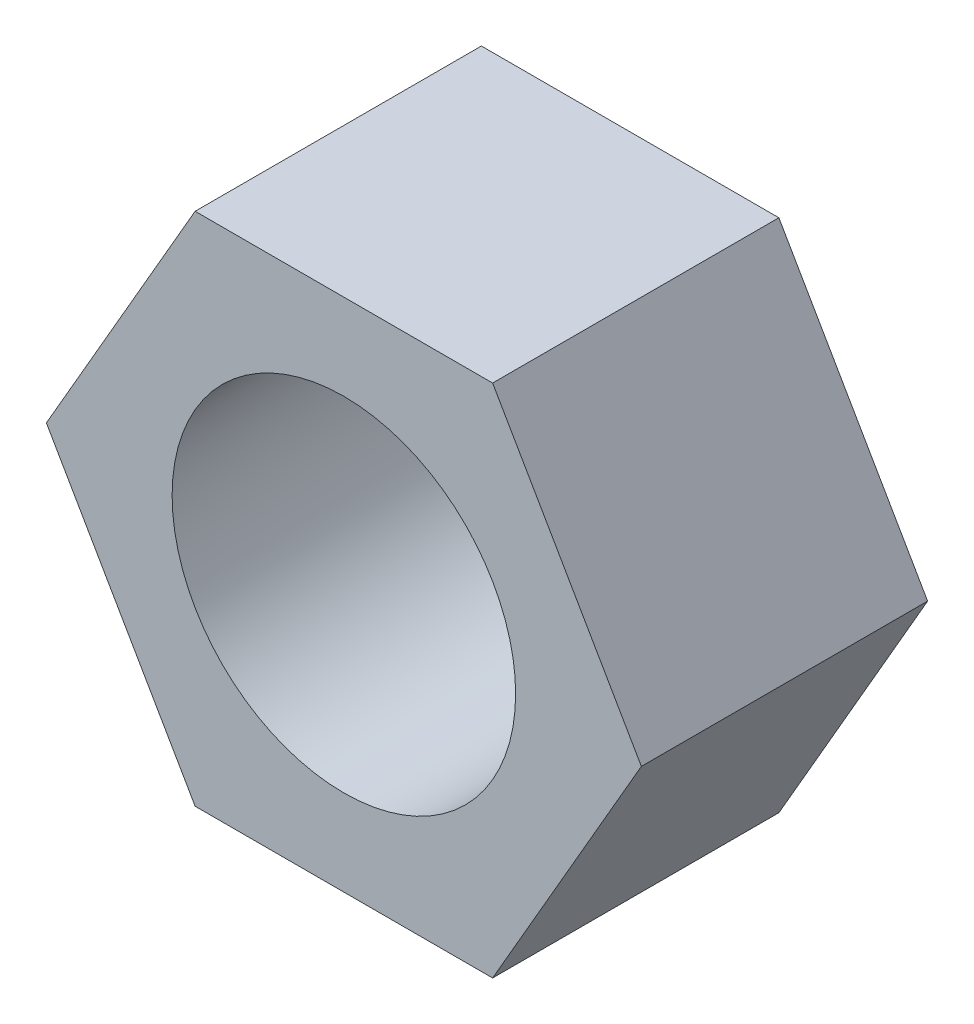
SolidWorks part; units mm, degrees
ref_plane "정면" through (0, 0, 0) normal (0, 0, 1) x (1, 0, 0)
ref_plane "윗면" through (0, 0, 0) normal (0, 1, 0) x (1, 0, 0)
ref_plane "우측면" through (0, 0, 0) normal (1, 0, 0) x (0, 0, -1)
sketch "스케치1" plane through (0, 0, 0) normal (0, 0, 1) x (1, 0, 0)
  line L1 (2.5981, -4.5) -> (5.1962, 0)
  line L2 (5.1962, 0) -> (2.5981, 4.5)
  line L3 (2.5981, 4.5) -> (-2.5981, 4.5)
  line L4 (-2.5981, 4.5) -> (-5.1962, 0)
  line L5 (-5.1962, 0) -> (-2.5981, -4.5)
  line L6 (-2.5981, -4.5) -> (2.5981, -4.5)
  circle A0 centre (0, 0) radius 4.5 construction
  circle A1 centre (0, 0) radius 3
  dimension "D1" = 6
  dimension "D2" = 9
extrude "보스-돌출1" add sketch "스케치1" along normal blind 5
